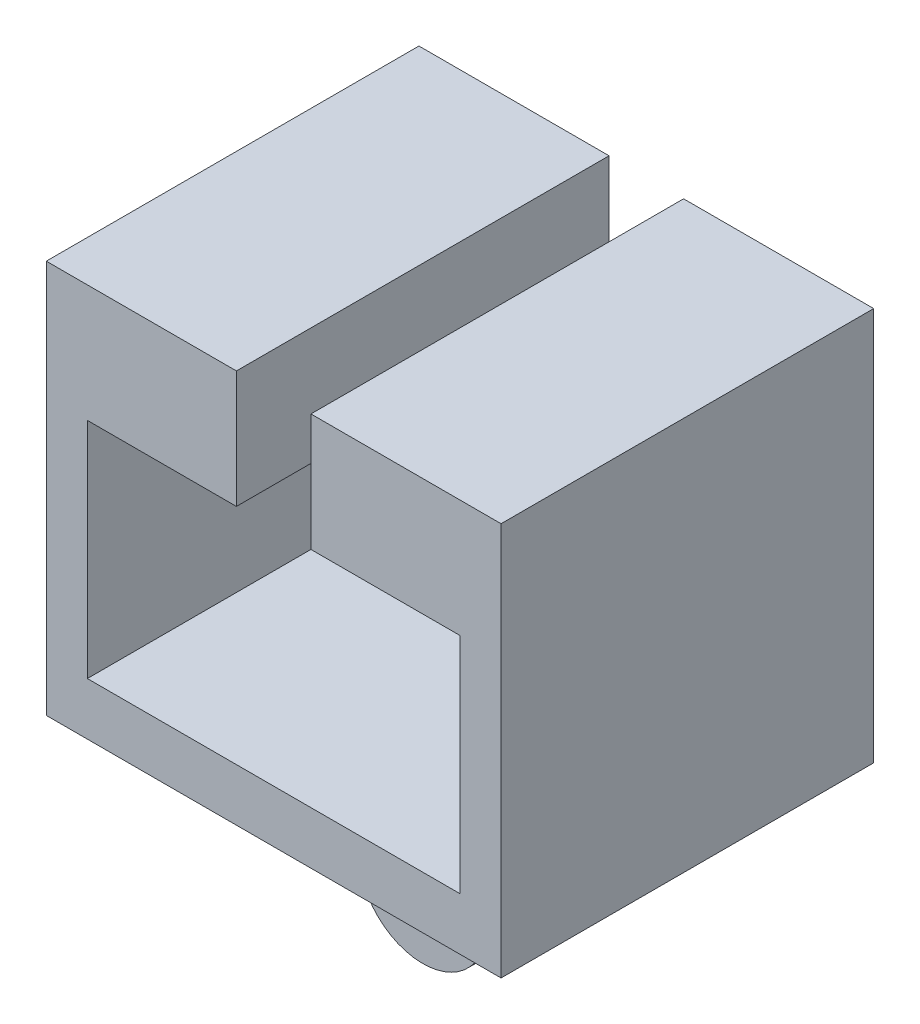
SolidWorks part; units mm, degrees
ref_plane "Front Plane" through (0, 0, 0) normal (0, 0, 1) x (1, 0, 0)
ref_plane "Top Plane" through (0, 0, 0) normal (0, 1, 0) x (1, 0, 0)
ref_plane "Right Plane" through (0, 0, 0) normal (1, 0, 0) x (0, 0, -1)
sketch "Sketch1" plane through (0, 0, 0) normal (0, 0, 1) x (1, 0, 0)
  circle A0 centre (0, 0) radius 10.895
  dimension "D1" = 21.7901
extrude "Boss-Extrude1" add sketch "Sketch1" against normal blind 38.1
sketch "Sketch2" plane through (0, 0, -38.1) normal (0, 0, -1) x (-1, 0, 0)
  line L0 (-11.176, 0) -> (11.176, 0)
  line L1 (-11.176, 0) -> (-11.176, 19.05)
  line L2 (11.176, 0) -> (11.176, 19.05)
  line L3 (-11.176, 19.05) -> (11.176, 19.05)
  point P5 (0, 0)
  dimension "D1" = 22.352
  dimension "D2" = 19.05
extrude "Boss-Extrude2" add sketch "Sketch2" against normal blind 2.4469
sketch "Sketch3" plane through (0, 0, -38.1) normal (0, 0, -1) x (-1, 0, 0)
  line L0 (-31.75, 19.05) -> (31.75, 19.05)
  line L2 (11.176, 19.05) -> (-11.176, 19.05) construction
  line L3 (-31.75, 19.05) -> (-31.75, 27.9931)
  line L4 (31.75, 19.05) -> (31.75, 27.9931)
  line L5 (-31.75, 27.9931) -> (31.75, 27.9931)
  point P3 (0, 19.05)
  dimension "D1" = 63.5
  dimension "D2" = 8.9431
extrude "Boss-Extrude3" add sketch "Sketch3" against normal blind 63.5
sketch "Sketch4" plane through (0, 0, -38.1) normal (0, 0, -1) x (-1, 0, 0)
  line L0 (-31.75, 27.9931) -> (-31.75, 66.0931)
  line L1 (-31.75, 66.0931) -> (-6.35, 66.0931)
  line L2 (-6.35, 66.0931) -> (-6.35, 86.0904)
  line L3 (31.75, 27.9931) -> (31.75, 66.0931)
  line L4 (31.75, 66.0931) -> (6.35, 66.0931)
  line L5 (6.35, 66.0931) -> (6.35, 86.0904)
  line L6 (6.35, 86.0904) -> (38.7472, 86.0904)
  line L7 (38.7472, 86.0904) -> (38.7472, 19.05)
  line L8 (31.75, 19.05) -> (38.7472, 19.05)
  line L9 (-31.75, 19.05) -> (-38.7472, 19.05)
  line L10 (-6.35, 86.0904) -> (-38.7472, 86.0904)
  line L11 (-38.7472, 19.05) -> (-38.7472, 86.0904)
  line L12 (-31.75, 19.05) -> (-31.75, 27.9931)
  line L13 (31.75, 19.05) -> (31.75, 27.9931)
  dimension "D4" = 38.1
  dimension "D2" = 19.9973
  dimension "D3" = 6.9972
  dimension "D1" = 25.4
extrude "Boss-Extrude4" add sketch "Sketch4" against normal blind 63.5
equation "\"F_1\"= 750"
equation "\"Sy\"= 36300"
equation "\"E\"= 29000000"
equation "\"N\"= 4"
equation "\"L_a\"= 1.5"
equation "\"W_b\"= 0.88"
equation "\"L_b\"= 0.75"
equation "\"F_2\"= 375"
equation "\"L\"= 2.5"
equation "\"B_c\"= 2.5"
equation "\"H_d\"= 1.5"
equation "\"S_allow\"= \"Sy\" / \"N\""
equation "\"B_e\"= 1"
equation "\"M_a\"= \"F_1\" * ( \"L_a\" / 2 )"
equation "\"M_c\"= ( \"F_1\" * \"L\" ) / 4"
equation "\"M_d\"= \"F_2\" * \"L\""
equation "\"M_e\"= \"F_2\" * \"L\""
equation "\"d_a\"= ( ( 32 * \"M_a\" ) / ( PI * \"S_allow\" ) ) ^ ( 1 / 3 )"
equation "\"T_b\"= \"F_1\" / ( \"d_a\" * \"S_allow\" )"
equation "\"H_c\"= sqr ( ( 6 * \"M_c\" ) / ( \"B_c\" * \"S_allow\" ) )"
equation "\"B_d\"= ( 6 * \"M_d\" ) / ( ( \"H_d\" ) ^ 2 * \"S_allow\" )"
equation "\"H_e\"= sqr ( ( 6 * \"M_e\" ) / ( \"B_e\" * \"S_allow\" ) )"
equation "\"D1@Sketch1\"=\"d_a\""
equation "\"D1@Boss-Extrude1\"=\"L_a\""
equation "\"D2@Sketch2\"=\"L_b\""
equation "\"D1@Sketch2\"=\"W_b\""
equation "\"D1@Boss-Extrude2\"=\"T_b\""
equation "\"D1@Sketch3\"=\"B_c\""
equation "\"D2@Sketch3\"=\"H_c\""
equation "\"D1@Boss-Extrude3\"=\"L\""
equation "\"D1@Sketch4\"=\"B_e\""
equation "\"D2@Sketch4\"=\"H_e\""
equation "\"D3@Sketch4\"=\"B_d\""
equation "\"D4@Sketch4\"=\"H_d\""
equation "\"D1@Boss-Extrude4\"=\"L\""
